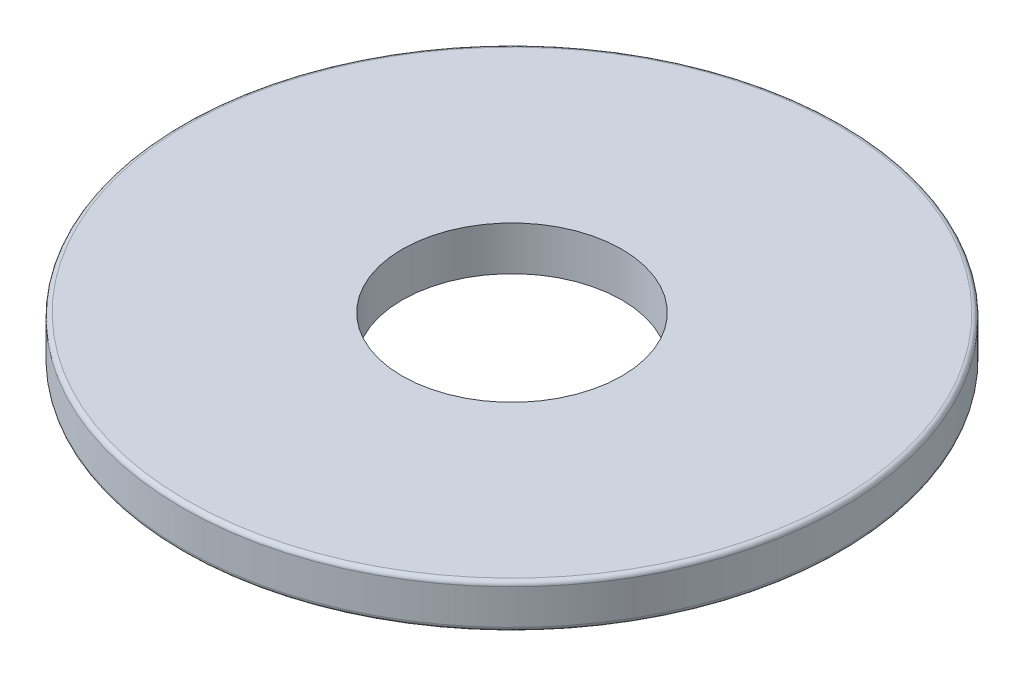
SolidWorks part; units mm, degrees
ref_plane "前视基准面" through (0, 0, 0) normal (0, 0, 1) x (1, 0, 0)
ref_plane "上视基准面" through (0, 0, 0) normal (0, 1, 0) x (1, 0, 0)
ref_plane "右视基准面" through (0, 0, 0) normal (1, 0, 0) x (0, 0, -1)
sketch "草图1" plane through (0, 0, 0) normal (0, 1, 0) x (1, 0, 0)
  circle A0 centre (0, 0) radius 5
  circle A1 centre (0, 0) radius 15
  dimension "D1" = 10
  dimension "D2" = 30
extrude "凸台-拉伸1" add sketch "草图1" along normal blind 2
fillet "圆角1" radius 0.2 2 edges at (0, 0, 15) (0, 2, 15)
